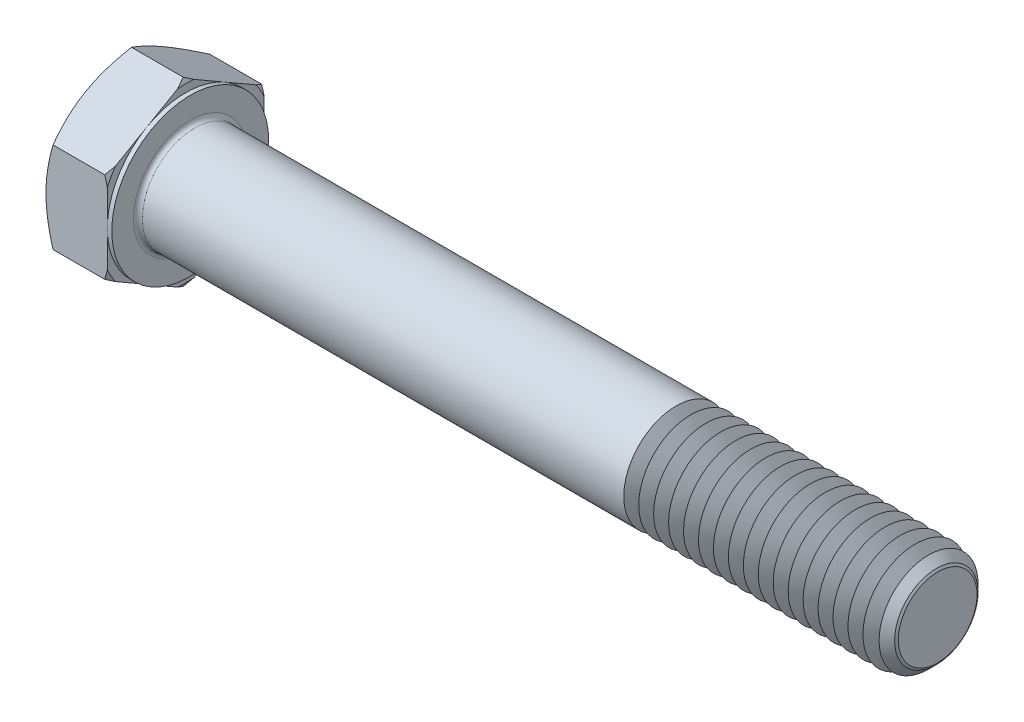
SolidWorks part; units mm, degrees
extrude "基体-拉伸" add sketch "草图1" along normal blind 8.8
sketch "草图1" plane through (0, 0, 0) normal (1, 0, 0) x (0, 0, -1)
  line L0 (10.5, 6.0622) -> (10.5, -6.0622)
  line L1 (-10.5, 6.0622) -> (-10.5, -6.0622)
  line L2 (10.5, -6.0622) -> (0, -12.1244)
  line L3 (0, -12.1244) -> (-10.5, -6.0622)
  line L4 (10.5, 6.0622) -> (0, 12.1244)
  line L5 (0, 12.1244) -> (-10.5, 6.0622)
  dimension "s" = 21
  dimension "D2" = 120
  dimension "D3" = 10.5
  dimension "D4" = 10.5
  dimension "D5" = 10.5
revolve "切除-旋转1" cut sketch "草图3" angle 360 about L6
sketch "草图3" plane through (0, 0, 0) normal (0, 0, 1) x (1, 0, 0)
  line L0 (0, 10.5) -> (3.8246, 17.1244)
  line L1 (0, 12.1244) -> (0, 6.0622) construction
  line L2 (3.8246, 17.1244) -> (3.8246, 22.1244)
  line L3 (3.8246, 22.1244) -> (-10, 22.1244)
  line L4 (-10, 22.1244) -> (-10, 10.5)
  line L5 (-10, 10.5) -> (0, 10.5)
  line L6 (0, 0) -> (99.06, 0) construction
  line L7 (8.8, 12.1244) -> (0, 12.1244) construction
  dimension "D1" = 10.5
  dimension "D2" = 5
  dimension "D3" = 10
  dimension "D4" = 5
  dimension "Head_ch_ang" = 30
material "3.6级"
ref_plane "前视" through (0, 0, 0) normal (0, 0, 1) x (1, 0, 0)
ref_plane "上视" through (0, 0, 0) normal (0, 1, 0) x (1, 0, 0)
ref_plane "右视" through (0, 0, 0) normal (1, 0, 0) x (0, 0, -1)
sketch "草图2" plane through (0, 0, 0) normal (0, 0, 1) x (1, 0, 0)
  line L0 (0, 6.0622) -> (0, -6.0622) construction
  line L1 (0, 0) -> (108.8, 0)
  line L2 (0, 0) -> (0, 7)
  line L3 (0, 7) -> (27.8072, 7)
  line L4 (108.8, 0) -> (108.8, 5.268)
  line L5 (8.8, 12.1244) -> (8.8, 6.0622) construction
  line L7 (0, 0) -> (96.52, 0) construction
  line L8 (108.8, -5.268) -> (27.8072, -7) construction
  line L9 (0, -7) -> (27.8072, -7) construction
  line L10 (10.8, 15.24) -> (10.8, -1.27) construction
  line L11 (74.8, 15.24) -> (74.8, -1.27) construction
  line L12 (8.8, 6.0622) -> (8.8, -6.0622) construction
  line L13 (27.8072, 7) -> (108.8, 7)
  line L14 (108.8, 7) -> (108.8, 5.268)
revolve "凸台-旋转1" add sketch "草图2" angle 360 about L7
cosmetic thread "螺旋线1" parameters "Thread_length"=34, "Thread_minor"=10.536
sketch "草图5" plane through (0, 0, 0) normal (0, 0, 1) x (1, 0, 0)
  line L0 (8.8, 10.5) -> (4.9754, 17.1244)
  line L1 (8.8, 12.1244) -> (8.8, 6.0622) construction
  line L2 (4.9754, 17.1244) -> (4.9754, 22.1244)
  line L3 (4.9754, 22.1244) -> (14.9754, 22.1244)
  line L4 (14.9754, 22.1244) -> (14.9754, 10.5)
  line L5 (14.9754, 10.5) -> (8.8, 10.5)
  line L7 (8.8, 12.1244) -> (0.9378, 12.1244) construction
  line L8 (0, 0) -> (99.06, 0) construction
  line L9 (0, 0) -> (99.06, 0) construction
  dimension "D1" = 10.5
  dimension "D2" = 5
  dimension "D3" = 10
  dimension "D4" = 5
  dimension "Head_ch_ang" = 30
revolve "切除-旋转2" cut sketch "草图5" angle 360 about L8
sketch "草图4" plane through (0, 0, 0) normal (0, 0, 1) x (1, 0, 0)
  line L1 (8.8, 12.1244) -> (8.8, 6.0622) construction
  line L2 (8.8, 10.5) -> (8.2, 10.5)
  line L3 (8.8, 10.5) -> (8.8, 22.1244)
  line L4 (8.8, 22.1244) -> (8.2, 22.1244)
  line L5 (0, 0) -> (95.25, 0) construction
  line L6 (0, 0) -> (96.52, 0) construction
  line L7 (8.2, 10.5) -> (8.2, 22.1244)
  line L8 (7.8622, 12.1244) -> (0.9378, 12.1244) construction
  dimension "D2" = 10
  dimension "D1" = 21
revolve "切除-旋转3" cut sketch "草图4" angle 360 about L5
chamfer "倒角" distance 1.6 angle 45 1 edges at (108.8, 0, 7)
fillet "圆角" radius 0.6 1 edges at (8.8, 0, -7)
sketch "草图6" plane through (0, 0, 0) normal (0, 0, 1) x (1, 0, 0)
  line L0 (74.8, -5.268) -> (73.8, -7)
  line L1 (74.8, -5.268) -> (75.8, -7)
  line L2 (75.8, -7) -> (75.8, -8.75)
  line L3 (-3.175, 0) -> (5.1513, 0) construction
  line L5 (75.8, -8.75) -> (73.8, -8.75)
  line L6 (73.8, -8.75) -> (73.8, -7)
  dimension "Thread_minor" = 10.536
  dimension "Diameter" = 14
  dimension "Start" = 74.8
revolve "切除-旋转4" cut sketch "草图6" angle 360 about L3
pattern_linear "阵列(线性)1" count 18 spacing 2 along (1, 0, 0) of "切除-旋转4"
equation "\"D3@草图1\" = \"s@草图1\" / 2"
equation "\"D4@草图1\" = \"D3@草图1\""
equation "\"D5@草图1\" = \"D4@草图1\""
equation "\"Thread_minor@螺旋线1\" = \"Minor_dia@草图2\""
equation "\"D1@草图3\" = \"s@草图1\" / 2"
equation "\"D1@草图5\" = \"s@草图1\" / 2"
equation "\"Head_ch_ang@草图5\" = \"Head_ch_ang@草图3\""
equation "\"D1@草图4\" = \"s@草图1\""
equation "\"Thread_length@螺旋线1\" = ((sgn( (\"l@草图2\" - \"p@草图2\" ) - \"h@草图2\" )-1)*( (\"l@草图2\" - \"p@草图2\" ) - \"h@草图2\" ))/-2+ \"h@草图2\""
equation "\"Thread_minor@草图6\" = \"Minor_dia@草图2\""
equation "\"Diameter@草图6\" = \"m@草图2\""
equation "\"Overcut@草图6\" = \"m@草图2\" * 1.25"
equation "\"Start@草图6\" = \"k@基体-拉伸\" + \"l@草图2\" - \"Thread_length@螺旋线1\"  '---Non-countersunk---"
equation "\"Num_threads@阵列(线性)1\" = int( \"Thread_length@螺旋线1\" / \"p@草图2\" + 0.999 )  + 1"
equation "\"Advance@阵列(线性)1\" = \"Thread_length@螺旋线1\" /  (\"Num_threads@阵列(线性)1\" - 1) 'relax it"
equation "\"Num_threads@阵列(线性)1\" = \"Num_threads@阵列(线性)1\" - sgn( \"Num_threads@阵列(线性)1\" - 1) '---chamfered tips only---"
equation "\"Minor_dia@草图2\" = \"m@草图2\"-\"p@草图2\" * 1.732"
equation "\"D1@倒角\" = \"p@草图2\"*0.8"
